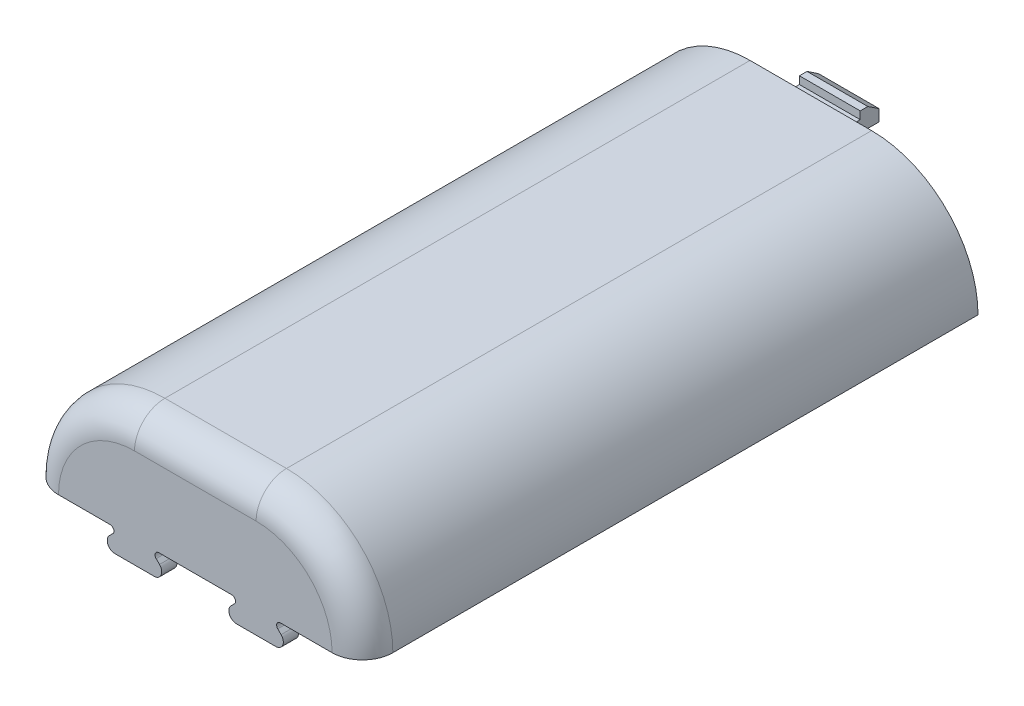
SolidWorks part; units mm, degrees
material "ABS"
ref_plane "前视基准面" through (0, 0, 0) normal (0, 0, 1) x (1, 0, 0)
ref_plane "上视基准面" through (0, 0, 0) normal (0, 1, 0) x (1, 0, 0)
ref_plane "右视基准面" through (0, 0, 0) normal (1, 0, 0) x (0, 0, -1)
sketch "草图1" plane through (0, 0, 0) normal (0, 0, 1) x (1, 0, 0)
  line L0 (0, 0) -> (8, 0)
  line L1 (0, 0) -> (-8, 0)
  line L2 (-8, 0) -> (-22, 0)
  line L5 (8, 0) -> (22, 0)
  line L6 (-8, 14) -> (8, 14)
  arc A0 (-22, 0) -> (-8, 14) centre (-8, 0) cw
  arc A1 (22, 0) -> (8, 14) centre (8, 0) ccw
extrude "凸台-拉伸1" add sketch "草图1" against normal blind 81
shell "抽壳1" thickness 2
fillet "圆角1" radius 4 3 edges at (17.8995, 9.8995, 0) (0, 14, 0) (-17.8995, 9.8995, 0)
fillet "圆角2" radius 2 3 edges at (16.4853, 8.4853, -2) (0, 12, -2) (-16.4853, 8.4853, -2)
sketch "草图2" plane through (0, 0, -81) normal (0, 0, -1) x (-1, 0, 0)
  line L0 (-20, 0) -> (-21.05, 0)
  line L2 (-20, 0) -> (-22, 0) construction
  line L3 (20, 0) -> (21.05, 0)
  line L4 (18, 0) -> (-18, 0) construction
  line L5 (-21.05, 0) -> (-20.9924, 1.0985)
  line L6 (-20.9924, 1.0985) -> (-19.9496, 1.0985)
  line L8 (22, 0) -> (20, 0) construction
  line L10 (21.05, 0) -> (20.9924, 1.0985)
  line L11 (20.9924, 1.0985) -> (19.9496, 1.0985)
  arc A0 (-20, 0) -> (-19.9496, 1.0985) centre (-8, 0) cw
  arc A1 (20, 0) -> (19.9496, 1.0985) centre (8, 0) ccw
extrude "切除-拉伸1" cut sketch "草图2" against normal blind 76.5
sketch "草图3" plane through (0, 0, 0) normal (1, 0, 0) x (0, 0, -1)
  line L0 (81, 12) -> (81, 13)
  line L2 (81, 0) -> (81, 14) construction
  line L3 (81, 13) -> (78, 13)
  line L4 (78, 13) -> (78, 10.5)
  line L5 (78, 10.5) -> (81, 10.5)
  line L6 (81, 10.5) -> (86, 10.5)
  line L7 (86, 10.5) -> (86, 12)
  line L8 (84.5, 13) -> (86, 12)
  line L9 (83.5, 12) -> (83.5, 13)
  line L10 (83.5, 13) -> (84.5, 13)
  line L12 (83.5, 12) -> (81, 12)
extrude "凸台-拉伸2" add sketch "草图3" along normal mid plane 8
sketch "草图4" plane through (0, 0, 0) normal (0, 0, 1) x (1, 0, 0)
  line L0 (0, 0) -> (0, 15.35) construction
  line L2 (-8, 0) -> (-6, 0)
  line L3 (-8, 0) -> (-10, 0)
  line L4 (-18, 0) -> (18, 0) construction
  line L5 (3, -3) -> (6, 0)
  line L6 (-10, -3) -> (-13, -3)
  line L7 (-13, -3) -> (-10, 0)
  line L8 (10, -3) -> (6, -3)
  line L9 (-6, -3) -> (-3, -3)
  line L10 (-10, -3) -> (-6, -3)
  line L11 (-3, -3) -> (-6, 0)
  line L12 (6, -3) -> (3, -3)
  line L13 (13, -3) -> (10, 0)
  line L14 (10, -3) -> (13, -3)
  line L15 (8, 0) -> (10, 0)
  line L16 (8, 0) -> (6, 0)
extrude "凸台-拉伸3" add sketch "草图4" against normal blind 2
fillet "圆角3" radius 1 4 edges at (13, -3, -1) (3, -3, -1) (-13, -3, -1) (-3, -3, -1)
fillet "圆角4" radius 0.5 4 edges at (-10, 0, -1) (-6, 0, -1) (6, 0, -1) (10, 0, -1)
